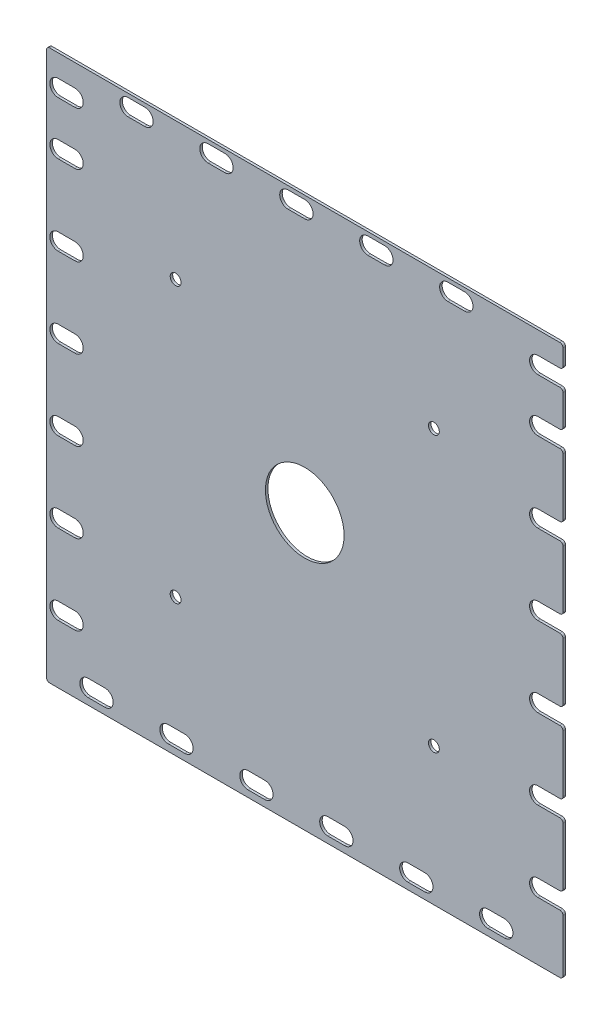
SolidWorks part; units mm, degrees
material "6061 Alloy"
ref_plane "Front Plane" through (0, 0, 0) normal (0, 0, 1) x (1, 0, 0)
ref_plane "Top Plane" through (0, 0, 0) normal (0, 1, 0) x (1, 0, 0)
ref_plane "Right Plane" through (0, 0, 0) normal (1, 0, 0) x (0, 0, -1)
sketch "Sketch1" plane through (0, 0, 0) normal (0, 0, 1) x (1, 0, 0)
  line L0 (0, 0) -> (0, -174.745)
  line L3 (0, -174.745) -> (165.1, -174.745)
  line L5 (0, 0) -> (165.1, 0)
  line L6 (165.1, -174.745) -> (165.1, 0)
  line L7 (82.55, 0) -> (82.55, -174.745) construction
  line L8 (31.75, -1.2) -> (26.45, -1.2)
  line L9 (31.75, -6.5) -> (26.45, -6.5)
  line L10 (9.525, -23.87) -> (4.225, -23.87)
  line L11 (9.525, -29.17) -> (4.225, -29.17)
  line L12 (161.925, -23.87) -> (156.625, -23.87)
  line L13 (161.925, -29.17) -> (156.625, -29.17)
  line L14 (57.15, -1.2) -> (51.85, -1.2)
  line L15 (57.15, -6.5) -> (51.85, -6.5)
  line L16 (82.55, -1.2) -> (77.25, -1.2)
  line L17 (82.55, -6.5) -> (77.25, -6.5)
  line L18 (107.95, -1.2) -> (102.65, -1.2)
  line L19 (107.95, -6.5) -> (102.65, -6.5)
  line L20 (133.35, -1.2) -> (128.05, -1.2)
  line L21 (133.35, -6.5) -> (128.05, -6.5)
  line L22 (9.525, -49.27) -> (4.225, -49.27)
  line L23 (9.525, -54.57) -> (4.225, -54.57)
  line L24 (161.925, -49.27) -> (156.625, -49.27)
  line L25 (161.925, -54.57) -> (156.625, -54.57)
  line L26 (9.525, -74.67) -> (4.225, -74.67)
  line L27 (9.525, -79.97) -> (4.225, -79.97)
  line L28 (161.925, -74.67) -> (156.625, -74.67)
  line L29 (161.925, -79.97) -> (156.625, -79.97)
  line L30 (9.525, -100.07) -> (4.225, -100.07)
  line L31 (9.525, -105.37) -> (4.225, -105.37)
  line L32 (161.925, -100.07) -> (156.625, -100.07)
  line L33 (161.925, -105.37) -> (156.625, -105.37)
  line L34 (9.525, -125.47) -> (4.225, -125.47)
  line L35 (9.525, -130.77) -> (4.225, -130.77)
  line L36 (161.925, -125.47) -> (156.625, -125.47)
  line L37 (161.925, -130.77) -> (156.625, -130.77)
  line L38 (9.525, -150.87) -> (4.225, -150.87)
  line L39 (9.525, -156.17) -> (4.225, -156.17)
  line L40 (161.925, -150.87) -> (156.625, -150.87)
  line L41 (161.925, -156.17) -> (156.625, -156.17)
  line L42 (19.05, -167.3325) -> (13.75, -167.3325)
  line L43 (19.05, -172.6325) -> (13.75, -172.6325)
  line L44 (44.45, -167.3325) -> (39.15, -167.3325)
  line L45 (44.45, -172.6325) -> (39.15, -172.6325)
  line L46 (69.85, -167.3325) -> (64.55, -167.3325)
  line L47 (69.85, -172.6325) -> (64.55, -172.6325)
  line L48 (95.25, -167.3325) -> (89.95, -167.3325)
  line L49 (95.25, -172.6325) -> (89.95, -172.6325)
  line L50 (120.65, -167.3325) -> (115.35, -167.3325)
  line L51 (120.65, -172.6325) -> (115.35, -172.6325)
  line L52 (146.05, -167.3325) -> (140.75, -167.3325)
  line L53 (146.05, -172.6325) -> (140.75, -172.6325)
  line L54 (0.5, 0) -> (0.5, -174.745)
  line L55 (164.6, -174.745) -> (164.6, 0)
  line L56 (0.5, -174.745) -> (164.6, -174.745)
  line L57 (9.525, -7.0375) -> (4.225, -7.0375)
  line L58 (9.525, -12.3375) -> (4.225, -12.3375)
  line L59 (161.925, -7.0375) -> (156.625, -7.0375)
  line L60 (161.925, -12.3375) -> (156.625, -12.3375)
  circle A41 centre (9.525, -153.52) radius 2.65
  circle A42 centre (19.05, -169.9825) radius 2.65
  circle A43 centre (9.525, -128.12) radius 2.65
  circle A44 centre (9.525, -102.72) radius 2.65
  circle A45 centre (9.525, -77.32) radius 2.65
  circle A46 centre (9.525, -51.92) radius 2.65
  circle A47 centre (9.525, -26.52) radius 2.65
  circle A49 centre (44.45, -169.9825) radius 2.65
  circle A50 centre (69.85, -169.9825) radius 2.65
  circle A51 centre (95.25, -169.9825) radius 2.65
  circle A52 centre (120.65, -169.9825) radius 2.65
  circle A68 centre (146.05, -169.9825) radius 2.65
  circle A69 centre (107.95, -3.85) radius 2.65
  circle A70 centre (82.55, -3.85) radius 2.65
  circle A71 centre (57.15, -3.85) radius 2.65
  circle A72 centre (9.525, -1.12) radius 2.65 [skipped]
  circle A73 centre (133.35, -3.85) radius 2.65
  circle A74 centre (31.75, -3.85) radius 2.65
  circle A75 centre (161.925, -26.52) radius 2.65
  circle A76 centre (161.925, -51.92) radius 2.65
  circle A77 centre (161.925, -77.32) radius 2.65
  circle A78 centre (161.925, -102.72) radius 2.65
  circle A79 centre (161.925, -128.12) radius 2.65
  circle A80 centre (161.925, -153.52) radius 2.65
  circle A81 centre (26.45, -3.85) radius 2.65
  circle A83 centre (4.225, -26.52) radius 2.65
  circle A84 centre (156.625, -26.52) radius 2.65
  circle A85 centre (51.85, -3.85) radius 2.65
  circle A86 centre (77.25, -3.85) radius 2.65
  circle A87 centre (102.65, -3.85) radius 2.65
  circle A88 centre (128.05, -3.85) radius 2.65
  circle A89 centre (4.225, -51.92) radius 2.65
  circle A90 centre (156.625, -51.92) radius 2.65
  circle A91 centre (4.225, -77.32) radius 2.65
  circle A92 centre (156.625, -77.32) radius 2.65
  circle A93 centre (4.225, -102.72) radius 2.65
  circle A94 centre (156.625, -102.72) radius 2.65
  circle A95 centre (4.225, -128.12) radius 2.65
  circle A96 centre (156.625, -128.12) radius 2.65
  circle A97 centre (4.225, -153.52) radius 2.65
  circle A98 centre (156.625, -153.52) radius 2.65
  circle A99 centre (13.75, -169.9825) radius 2.65
  circle A100 centre (39.15, -169.9825) radius 2.65
  circle A101 centre (64.55, -169.9825) radius 2.65
  circle A102 centre (89.95, -169.9825) radius 2.65
  circle A103 centre (115.35, -169.9825) radius 2.65
  circle A104 centre (140.75, -169.9825) radius 2.65
  circle A105 centre (82.55, -87.3725) radius 12.5
  circle A107 centre (9.525, -9.6875) radius 2.65
  circle A108 centre (4.225, -9.6875) radius 2.65
  circle A109 centre (161.925, -9.6875) radius 2.65
  circle A110 centre (156.625, -9.6875) radius 2.65
  dimension "D3" = 5.3
  dimension "D8" = 5.3
  dimension "D21" = 5.3
  dimension "D31" = 25
  dimension "D33" = 5.3
  dimension "D1" = 165.1
  dimension "D2" = 174.745
  dimension "D5" = 9.525
  dimension "D4" = 21.225
  dimension "D6" = 19.05
  dimension "D7" = 4.7625
  dimension "D9" = 25.4
  dimension "D10" = 25.4
  dimension "D15" = 25.4
  dimension "D12" = 3.85
  dimension "D13" = 31.75
  dimension "D17" = 31.75
  dimension "D18" = 3.175
  dimension "D20" = 25.4
  dimension "D23" = 25.4
  dimension "D25" = 25.4
  dimension "D27" = 25.4
  dimension "D28" = 0.5
  dimension "D29" = 0.5
  dimension "D30" = 87.3725
  dimension "D34" = 16.8325
  dimension "D35" = 5.8375
  dimension "D11" = 7
  dimension "D14" = 5
  dimension "D16" = 5
  dimension "D19" = 6
  dimension "D22" = 5
  dimension "D24" = 6
  dimension "D26" = 6
extrude "Boss-Extrude1" add sketch "Sketch1" along normal blind 0.8 contours L7 L5 L0 L3 A50 A41 A42 A43 A44 A45 A46 A47 A73 A49 | L5 L7 A70 A105 L56 L55 A84 L12 A75 L13 A87 L18 A69 L19 A88 L20 A73 L21 A90 L24 A76 L25 A92 L28 A77 L29 A94 L32 A78 L33 A96 L36 A79 L37 A98 L40 A80 L41 A102 L48
fillet "Fillet1" radius 1 4 edges at (164.6, 0, 0.4) (164.6, -174.745, 0.4) (0.5, -174.745, 0.4) (0.5, 0, 0.4)
sketch "Sketch2" plane through (0, 0, 0.8) normal (0, 0, 1) x (1, 0, 0)
  line L0 (1.5, 0) -> (163.6, 0) construction
  line L1 (41.525, -43.6863) -> (123.575, -43.6863) construction
  line L2 (41.525, -43.6863) -> (41.525, -131.0588) construction
  line L3 (41.525, -131.0588) -> (123.575, -131.0588) construction
  line L4 (123.575, -43.6863) -> (123.575, -131.0588) construction
  line L5 (41.525, -43.6863) -> (123.575, -131.0588) construction
  line L6 (41.525, -131.0588) -> (123.575, -43.6863) construction
  line L7 (0.5, -1) -> (164.6, -1) construction
  line L8 (1.5, 0) -> (1.5, -174.745) construction
  line L14 (164.6, -173.745) -> (164.6, -1) construction
  line L19 (161.925, -7.0375) -> (164.6, -7.0375)
  line L20 (161.925, -7.0375) -> (161.925, -12.3375)
  line L21 (161.925, -12.3375) -> (164.6, -12.3375)
  line L22 (164.6, -7.0375) -> (164.6, -12.3375)
  line L23 (161.925, -49.27) -> (161.925, -54.57)
  line L24 (161.925, -23.87) -> (164.6, -23.87)
  line L25 (161.925, -23.87) -> (161.925, -29.17)
  line L26 (161.925, -29.17) -> (164.6, -29.17)
  line L27 (164.6, -23.87) -> (164.6, -29.17)
  line L28 (161.925, -49.27) -> (164.6, -49.27)
  line L29 (164.6, -49.27) -> (164.6, -54.57)
  line L30 (161.925, -54.57) -> (164.6, -54.57)
  line L31 (161.925, -74.67) -> (161.925, -79.97)
  line L32 (161.925, -74.67) -> (164.6, -74.67)
  line L33 (164.6, -74.67) -> (164.6, -79.97)
  line L34 (161.925, -79.97) -> (164.6, -79.97)
  line L35 (161.925, -100.07) -> (161.925, -105.37)
  line L36 (161.925, -100.07) -> (164.6, -100.07)
  line L37 (164.6, -100.07) -> (164.6, -105.37)
  line L38 (161.925, -105.37) -> (164.6, -105.37)
  line L39 (161.925, -125.47) -> (161.925, -130.77)
  line L40 (161.925, -125.47) -> (164.6, -125.47)
  line L41 (164.6, -125.47) -> (164.6, -130.77)
  line L42 (161.925, -130.77) -> (164.6, -130.77)
  line L43 (161.925, -150.87) -> (161.925, -156.17)
  line L44 (161.925, -150.87) -> (164.6, -150.87)
  line L45 (164.6, -150.87) -> (164.6, -156.17)
  line L46 (161.925, -156.17) -> (164.6, -156.17)
  circle A0 centre (41.525, -43.6863) radius 1.725
  circle A1 centre (123.575, -43.6863) radius 1.725
  circle A2 centre (123.575, -131.0588) radius 1.725
  circle A3 centre (41.525, -131.0588) radius 1.725
  arc A4 (161.925, -29.17) -> (161.925, -23.87) centre (161.925, -26.52) ccw construction
  point P4 (82.55, -87.3725)
  point P11 (82.55, 0)
  point P45 (161.925, -26.52)
  point P47 (161.925, -51.92)
  dimension "D1" = 3.45
  dimension "D2" = 164.1
  dimension "D3" = 174.745
  dimension "D4" = 41.025
  dimension "D5" = 43.6863
  dimension "D6" = 43.6863
  dimension "D8" = 25.4
  dimension "D7" = 6
extrude "Cut-Extrude1" cut sketch "Sketch2" against normal through all both
fillet "Fillet2" radius 1 14 edges at (164.6, -156.17, 0.4) (164.6, -150.87, 0.4) (164.6, -130.77, 0.4) (164.6, -125.47, 0.4) (164.6, -105.37, 0.4) (164.6, -100.07, 0.4) (164.6, -79.97, 0.4) (164.6, -74.67, 0.4) (164.6, -54.57, 0.4) (164.6, -49.27, 0.4) (164.6, -29.17, 0.4) (164.6, -23.87, 0.4) (164.6, -12.3375, 0.4) (164.6, -7.0375, 0.4)
equation "\"D29@Sketch1\"=\"D28@Sketch1\""
equation "\"D30@Sketch1\"=\"D2@Sketch1\"/2"
equation "\"D8@Sketch1\"=\"D3@Sketch1\""
equation "\"D4@Sketch2\"=\"D2@Sketch2\"/4"
equation "\"D5@Sketch2\"=\"D3@Sketch2\"/4"
equation "\"D6@Sketch2\"=\"D3@Sketch2\"/4"
